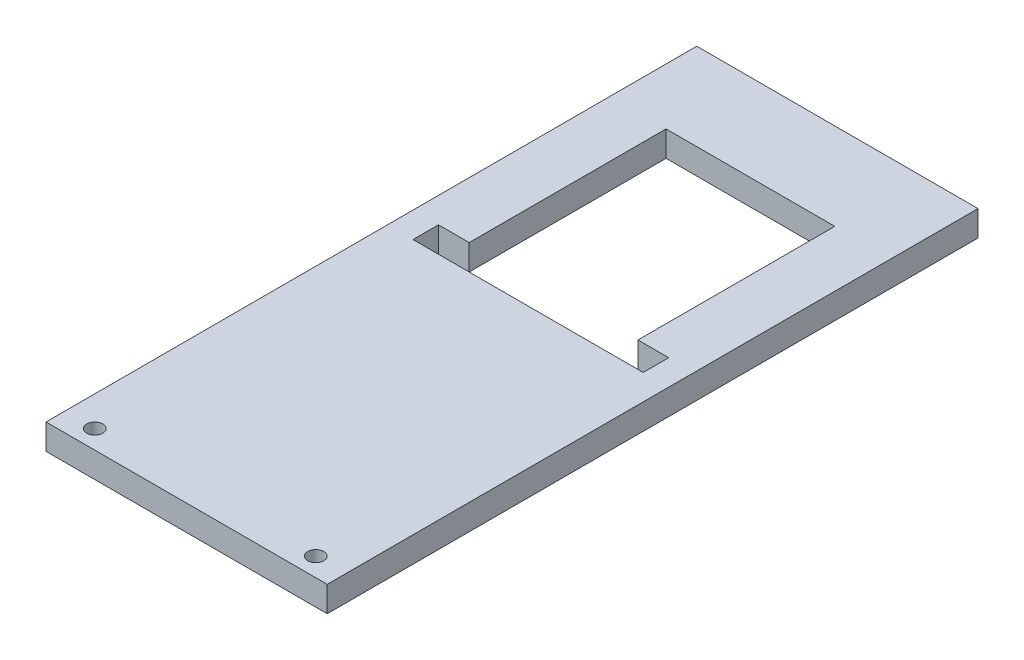
SolidWorks part; units mm, degrees
ref_plane "Front Plane" through (0, 0, 0) normal (0, 0, 1) x (1, 0, 0)
ref_plane "Top Plane" through (0, 0, 0) normal (0, 1, 0) x (1, 0, 0)
ref_plane "Right Plane" through (0, 0, 0) normal (1, 0, 0) x (0, 0, -1)
sketch "Sketch1" plane through (0, 0, 0) normal (0, 1, 0) x (1, 0, 0)
  line L0 (-35, 0) -> (-35, -200)
  line L1 (-35, -200) -> (35, -200)
  line L2 (35, -200) -> (35, 0)
  circle A0 centre (0, 0) radius 35
  point P3 (0, -200)
  dimension "D1" = 70
  dimension "D2" = 70
  dimension "D3" = 200
extrude "Boss-Extrude1" add sketch "Sketch1" along normal mid plane 6.35
sketch "Sketch2" plane through (0, 3.175, 0) normal (0, 1, 0) x (1, 0, 0)
  line L0 (35, -38) -> (-35, -38)
  line L1 (35, -200) -> (35, 0) construction
  line L2 (-35, 0) -> (-35, -200) construction
  line M1 (35, -200) -> (35, 0)
  arc M2 (35, 0) -> (-35, 0) centre (0, 0) ccw
  line M3 (-35, 0) -> (-35, -200)
  dimension "D1" = 38
extrude "Cut-Extrude1" cut sketch "Sketch2" against normal through all contours L0 M1 M2 M3
fillet "Fillet2" [suppressed] radius 8
sketch "Sketch3" plane through (0, 3.175, 0) normal (0, 1, 0) x (1, 0, 0)
  line L0 (-35, -200) -> (35, -200) construction
  line L1 (21, -115) -> (-21, -115)
  line L2 (21, -115) -> (21, -59.65)
  line L3 (21, -59.65) -> (-21, -59.65)
  line L4 (-21, -115) -> (-21, -59.65)
  line L5 (21, -115) -> (-21, -59.65) construction
  line L6 (21, -59.65) -> (-21, -115) construction
  line L8 (-21, -115) -> (-28.65, -115)
  line L9 (-21, -115) -> (-21, -108.65)
  line L10 (-21, -108.65) -> (-28.65, -108.65)
  line L11 (-28.65, -115) -> (-28.65, -108.65)
  line L12 (21, -115) -> (28.65, -115)
  line L13 (21, -115) -> (21, -108.65)
  line L14 (21, -108.65) -> (28.65, -108.65)
  line L15 (28.65, -115) -> (28.65, -108.65)
  point P0 (0, -87.325)
  point P8 (0, -200)
  dimension "D1" = 85
  dimension "D2" = 55.35
  dimension "D3" = 6.35
  dimension "42" = 42
  dimension "D4" = 7.65
extrude "Cut-Extrude2" cut sketch "Sketch3" against normal through all contours L4 L1 L2 L3 | L11 L8 L4 L10 | L12 L15 L14 L2
sketch "Sketch4" plane through (0, 0, 200) normal (0, 0, 1) x (1, 0, 0)
  line L0 (-35, 3.175) -> (35, 3.175) construction
  arc A0 (-4.7121, 3.175) -> (4.7121, 3.175) centre (0, 4.8471) ccw
  dimension "D1" = 5
extrude "Cut-Extrude3" [suppressed] cut sketch "Sketch4" against normal blind 10 and the other way through all
sketch "Sketch5" plane through (0, 3.175, 0) normal (0, 1, 0) x (1, 0, 0)
  circle A0 centre (27.5, -195.35) radius 2
  circle A1 centre (-27.5, -195.35) radius 2
  circle A2 centre (15, -65.35) radius 2
  circle A3 centre (-15, -65.35) radius 2
extrude "Cut-Extrude4" cut sketch "Sketch5" against normal through all
